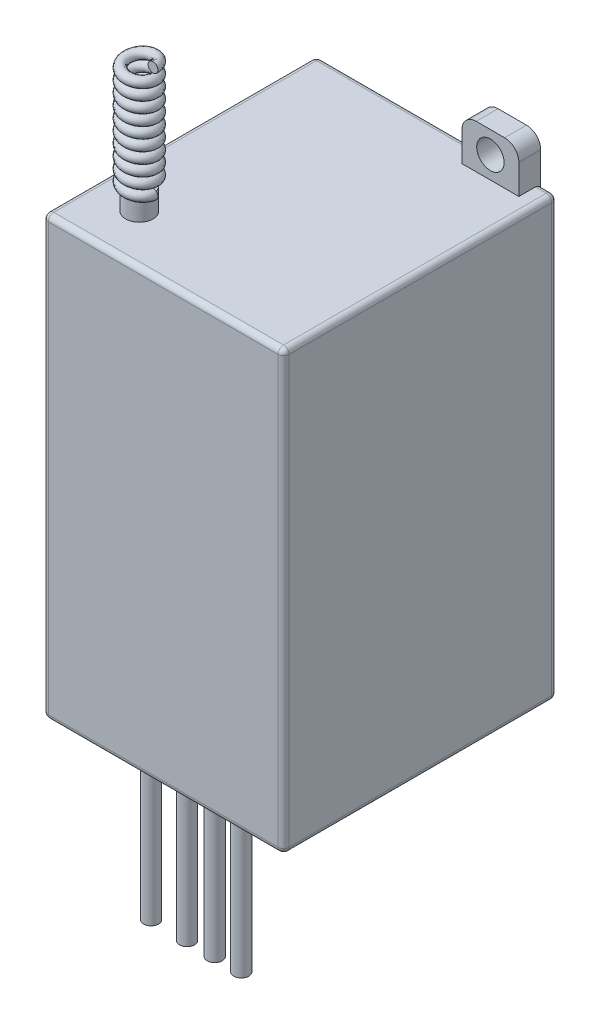
SolidWorks part; units mm, degrees
ref_plane "Front" through (0, 0, 0) normal (0, 0, 1) x (1, 0, 0)
ref_plane "Top" through (0, 0, 0) normal (0, 1, 0) x (1, 0, 0)
ref_plane "Right" through (0, 0, 0) normal (1, 0, 0) x (0, 0, -1)
sketch "Sketch1" plane through (0, 0, 0) normal (0, 0, 1) x (1, 0, 0)
  line L1 (-11, -20) -> (11, -20)
  line L2 (-11, -20) -> (-11, 20)
  line L3 (-11, 20) -> (11, 20)
  line L4 (11, -20) -> (11, 20)
  line L5 (-11, -20) -> (11, 20) construction
  line L6 (-11, 20) -> (11, -20) construction
  point P0 (0, 0)
  dimension "D1" = 22
  dimension "D2" = 40
extrude "Boss-Extrude1" add sketch "Sketch1" along normal blind 25
fillet "Body Fillets" radius 0.5 12 edges at (0, -20, 25) (0, -20, 0) (-11, 0, 25) (-11, -20, 12.5) (-11, 0, 0) (11, -20, 12.5) (11, 0, 25) (11, 0, 0) (11, 20, 12.5) (0, 20, 25) (-11, 20, 12.5) (0, 20, 0)
sketch "Sketch2" plane through (0, 0, 0) normal (0, 0, 1) x (1, 0, 0)
  line L0 (9.5, 19.5) -> (9.5, 22.7)
  line L1 (10.5, 19.5) -> (-10.5, 19.5) construction
  line L2 (8.2, 24) -> (5.6, 24)
  line L3 (4.3, 22.7) -> (4.3, 19.5)
  line L4 (4.3, 19.5) -> (9.5, 19.5)
  line L5 (6.9, 24) -> (6.9, 22) construction
  line L6 (-10.5, 20) -> (10.5, 20) construction
  line L7 (11, 19.5) -> (11, -19.5) construction
  arc A0 (9.5, 22.7) -> (8.2, 24) centre (8.2, 22.7) ccw
  arc A1 (5.6, 24) -> (4.3, 22.7) centre (5.6, 22.7) ccw
  circle A2 centre (6.9, 22) radius 1.25
  dimension "D1" = 1.3
  dimension "D4" = 2.5
  dimension "D2" = 4
  dimension "D3" = 1.5
  dimension "D5" = 2
extrude "Mounting Tab" add sketch "Sketch2" along normal blind 2
sketch "Sketch3" plane through (0, 20, 0) normal (0, 1, 0) x (1, 0, 0)
  circle A0 centre (-6.6849, -20.4976) radius 1.25
  dimension "D1" = 2.5
extrude "Antina base" add sketch "Sketch3" along normal blind 2
sketch "Sketch4" plane through (0, 22, 0) normal (0, 1, 0) x (1, 0, 0)
  circle A1 centre (-6.6849, -20.4976) radius 1.25
  circle A2 centre (-6.6849, -20.4976) radius 1.25
  dimension "D1" = 0
curve "Helix/Spiral1" pitch 1 height 10 turns 10
ref_plane "Plane1" through (0, 0, 20.4976) normal (0, 0, 1) x (1, 0, 0)
sketch "Sketch5" plane through (0, 0, 20.4976) normal (0, 0, 1) x (1, 0, 0)
  circle A0 centre (-5.4349, 32) radius 0.45
  dimension "D1" = 0.9
sweep "Sweep1" add profiles "Sketch5" path "Helix/Spiral1"
sketch "Sketch6" plane through (0, -20, 0) normal (0, -1, 0) x (1, 0, 0)
  circle A0 centre (-1.7731, 21.0489) radius 0.6875
  circle A1 centre (0.755, 21.0489) radius 0.6875
  circle A2 centre (3.1859, 21.0489) radius 0.6875
  circle A3 centre (-5.0629, 21.0489) radius 0.6875
extrude "Boss-Extrude4" add sketch "Sketch6" along normal blind 15
